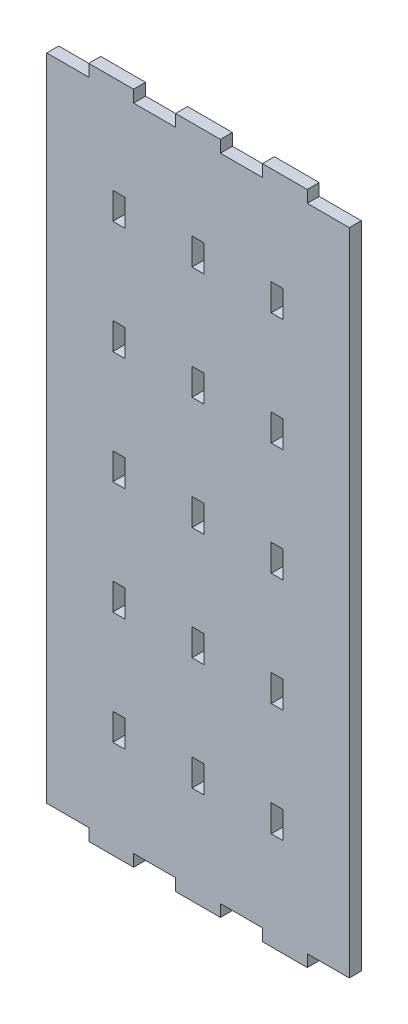
SolidWorks part; units mm, degrees
ref_plane "Front Plane" through (0, 0, 0) normal (0, 0, 1) x (1, 0, 0)
ref_plane "Top Plane" through (0, 0, 0) normal (0, 1, 0) x (1, 0, 0)
ref_plane "Right Plane" through (0, 0, 0) normal (1, 0, 0) x (0, 0, -1)
sketch "Model" plane through (0, 0, 0) normal (0, 0, 1) x (1, 0, 0)
  line L0 (105.525, 43.6833) -> (100.175, 43.6833)
  line L1 (105.525, 55.6833) -> (105.525, 43.6833)
  line L2 (100.175, 55.6833) -> (105.525, 55.6833)
  line L3 (100.175, 43.6833) -> (100.175, 55.6833)
  line L4 (105.525, 94.0167) -> (100.175, 94.0167)
  line L5 (105.525, 106.0167) -> (105.525, 94.0167)
  line L6 (100.175, 106.0167) -> (105.525, 106.0167)
  line L7 (100.175, 94.0167) -> (100.175, 106.0167)
  line L8 (105.525, 144.35) -> (100.175, 144.35)
  line L9 (105.525, 156.35) -> (105.525, 144.35)
  line L10 (100.175, 156.35) -> (105.525, 156.35)
  line L11 (100.175, 144.35) -> (100.175, 156.35)
  line L12 (105.525, 194.6833) -> (100.175, 194.6833)
  line L13 (105.525, 206.6833) -> (105.525, 194.6833)
  line L14 (100.175, 206.6833) -> (105.525, 206.6833)
  line L15 (100.175, 194.6833) -> (100.175, 206.6833)
  line L16 (105.525, 245.0167) -> (100.175, 245.0167)
  line L17 (105.525, 257.0167) -> (105.525, 245.0167)
  line L18 (100.175, 257.0167) -> (105.525, 257.0167)
  line L19 (100.175, 245.0167) -> (100.175, 257.0167)
  line L20 (70.175, 245.0167) -> (64.825, 245.0167)
  line L21 (70.175, 257.0167) -> (70.175, 245.0167)
  line L22 (64.825, 257.0167) -> (70.175, 257.0167)
  line L23 (64.825, 245.0167) -> (64.825, 257.0167)
  line L24 (70.175, 194.6833) -> (64.825, 194.6833)
  line L25 (70.175, 206.6833) -> (70.175, 194.6833)
  line L26 (64.825, 206.6833) -> (70.175, 206.6833)
  line L27 (64.825, 194.6833) -> (64.825, 206.6833)
  line L28 (70.175, 144.35) -> (64.825, 144.35)
  line L29 (70.175, 156.35) -> (70.175, 144.35)
  line L30 (64.825, 156.35) -> (70.175, 156.35)
  line L31 (64.825, 144.35) -> (64.825, 156.35)
  line L32 (70.175, 94.0167) -> (64.825, 94.0167)
  line L33 (70.175, 106.0167) -> (70.175, 94.0167)
  line L34 (64.825, 106.0167) -> (70.175, 106.0167)
  line L35 (64.825, 94.0167) -> (64.825, 106.0167)
  line L36 (70.175, 43.6833) -> (64.825, 43.6833)
  line L37 (70.175, 55.6833) -> (70.175, 43.6833)
  line L38 (64.825, 55.6833) -> (70.175, 55.6833)
  line L39 (64.825, 43.6833) -> (64.825, 55.6833)
  line L40 (34.825, 43.6833) -> (29.475, 43.6833)
  line L41 (34.825, 55.6833) -> (34.825, 43.6833)
  line L42 (29.475, 55.6833) -> (34.825, 55.6833)
  line L43 (29.475, 43.6833) -> (29.475, 55.6833)
  line L44 (34.825, 94.0167) -> (29.475, 94.0167)
  line L45 (34.825, 106.0167) -> (34.825, 94.0167)
  line L46 (29.475, 106.0167) -> (34.825, 106.0167)
  line L47 (29.475, 94.0167) -> (29.475, 106.0167)
  line L48 (34.825, 144.35) -> (29.475, 144.35)
  line L49 (34.825, 156.35) -> (34.825, 144.35)
  line L50 (29.475, 156.35) -> (34.825, 156.35)
  line L51 (29.475, 144.35) -> (29.475, 156.35)
  line L52 (34.825, 194.6833) -> (29.475, 194.6833)
  line L53 (34.825, 206.6833) -> (34.825, 194.6833)
  line L54 (29.475, 206.6833) -> (34.825, 206.6833)
  line L55 (29.475, 194.6833) -> (29.475, 206.6833)
  line L56 (34.825, 245.0167) -> (29.475, 245.0167)
  line L57 (34.825, 257.0167) -> (34.825, 245.0167)
  line L58 (29.475, 257.0167) -> (34.825, 257.0167)
  line L59 (29.475, 245.0167) -> (29.475, 257.0167)
  line L60 (0, 295.35) -> (0, 5.35)
  line L61 (18.75, 295.35) -> (0, 295.35)
  line L62 (18.75, 300.7) -> (18.75, 295.35)
  line L63 (38.75, 300.7) -> (18.75, 300.7)
  line L64 (38.75, 295.35) -> (38.75, 300.7)
  line L65 (57.5, 295.35) -> (38.75, 295.35)
  line L66 (57.5, 300.7) -> (57.5, 295.35)
  line L67 (77.5, 300.7) -> (57.5, 300.7)
  line L68 (77.5, 295.35) -> (77.5, 300.7)
  line L69 (96.25, 295.35) -> (77.5, 295.35)
  line L70 (96.25, 300.7) -> (96.25, 295.35)
  line L71 (116.25, 300.7) -> (96.25, 300.7)
  line L72 (116.25, 295.35) -> (116.25, 300.7)
  line L73 (135, 295.35) -> (116.25, 295.35)
  line L74 (135, 5.35) -> (135, 295.35)
  line L75 (116.25, 5.35) -> (135, 5.35)
  line L76 (116.25, 0) -> (116.25, 5.35)
  line L77 (96.25, 0) -> (116.25, 0)
  line L78 (96.25, 5.35) -> (96.25, 0)
  line L79 (77.5, 5.35) -> (96.25, 5.35)
  line L80 (77.5, 0) -> (77.5, 5.35)
  line L81 (57.5, 0) -> (77.5, 0)
  line L82 (57.5, 5.35) -> (57.5, 0)
  line L83 (38.75, 5.35) -> (57.5, 5.35)
  line L84 (38.75, 0) -> (38.75, 5.35)
  line L85 (18.75, 0) -> (38.75, 0)
  line L86 (18.75, 5.35) -> (18.75, 0)
  line L87 (0, 5.35) -> (18.75, 5.35)
extrude "Boss-Extrude1" add sketch "Model" along normal blind 5.35
